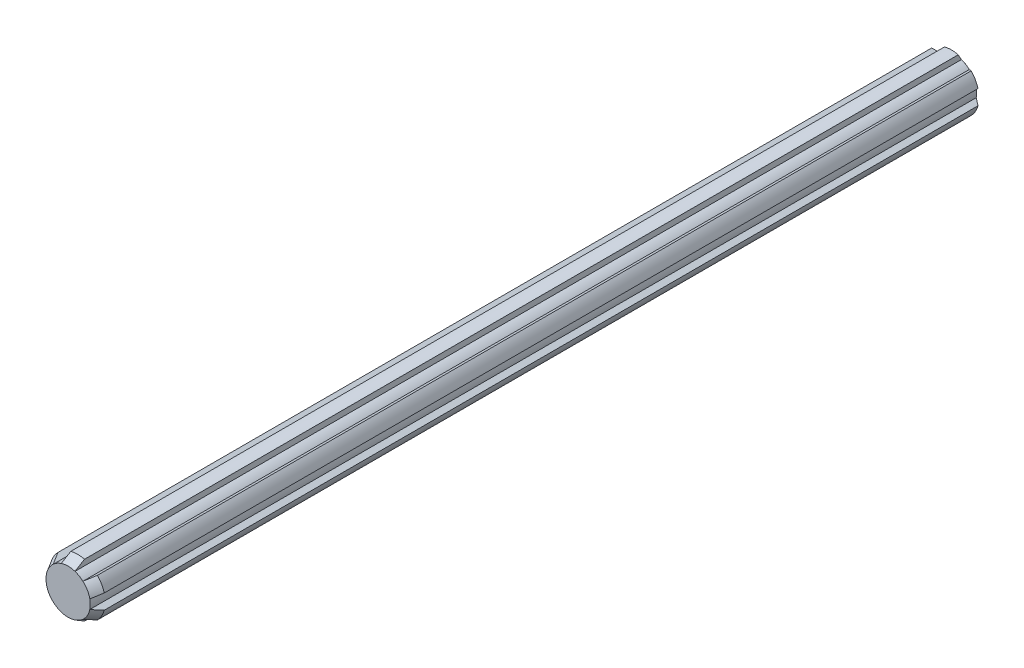
SolidWorks part; units mm, degrees
ref_plane "Front Plane" through (0, 0, 0) normal (0, 0, 1) x (1, 0, 0)
ref_plane "Top Plane" through (0, 0, 0) normal (0, 1, 0) x (1, 0, 0)
ref_plane "Right Plane" through (0, 0, 0) normal (1, 0, 0) x (0, 0, -1)
sketch "Sketch1" plane through (0, 0, 0) normal (0, 0, 1) x (1, 0, 0)
  circle A0 centre (0, 0) radius 17.435
  point P8 (0, 17.435)
  dimension "D1" = 34.87
extrude "Boss-Extrude2" add sketch "Sketch1" along normal blind 558.8
chamfer "Chamfer2" distance 6 angle 30 1 edges at (17.435, 0, 558.8)
chamfer "Chamfer3" distance 3.5 angle 30 1 edges at (17.435, 0, 0)
sketch "Sketch3" plane through (0, 0, 0) normal (0, 0, -1) x (-1, 0, 0)
  line L0 (-4.32, 16.8913) -> (-4.32, 13.259)
  line L1 (12.4683, 12.1869) -> (9.3226, 10.3707)
  line L2 (4.32, 16.8913) -> (4.32, 13.259)
  line L3 (16.7883, 4.7044) -> (13.6426, 2.8883)
  line L4 (16.7883, -4.7044) -> (13.6426, -2.8883)
  line L5 (12.4683, -12.1869) -> (9.3226, -10.3707)
  line L6 (4.32, -16.8913) -> (4.32, -13.259)
  line L7 (-4.32, -16.8913) -> (-4.32, -13.259)
  line L8 (-12.4683, -12.1869) -> (-9.3226, -10.3707)
  line L9 (-16.7883, -4.7044) -> (-13.6426, -2.8883)
  line L10 (-16.7883, 4.7044) -> (-13.6426, 2.8883)
  line L11 (-12.4683, 12.1869) -> (-9.3226, 10.3707)
  arc A0 (-13.6426, 2.8883) -> (-13.6426, -2.8883) centre (0, 0) ccw
  arc A3 (16.7883, -4.7044) -> (16.7883, 4.7044) centre (0, 0) ccw
  arc A4 (4.32, -16.8913) -> (12.4683, -12.1869) centre (0, 0) ccw
  arc A5 (-12.4683, -12.1869) -> (-4.32, -16.8913) centre (0, 0) ccw
  arc A6 (13.6426, -2.8883) -> (13.6426, 2.8883) centre (0, 0) ccw
  arc A7 (-4.32, 16.8913) -> (-12.4683, 12.1869) centre (0, 0) ccw
  arc A8 (-16.7883, 4.7044) -> (-16.7883, -4.7044) centre (0, 0) ccw
  arc A10 (12.4683, 12.1869) -> (4.32, 16.8913) centre (0, 0) ccw
  arc A11 (4.32, -13.259) -> (9.3226, -10.3707) centre (0, 0) ccw
  arc A12 (-9.3226, -10.3707) -> (-4.32, -13.259) centre (0, 0) ccw
  arc A13 (-4.32, 13.259) -> (-9.3226, 10.3707) centre (0, 0) ccw
  arc A14 (9.3226, 10.3707) -> (4.32, 13.259) centre (0, 0) ccw
  point P10 (2.16, 17.435)
  dimension "D1" = 27.89
  dimension "D2" = 6
extrude "Cut-Extrude1" cut sketch "Sketch3" against normal blind 558.8
